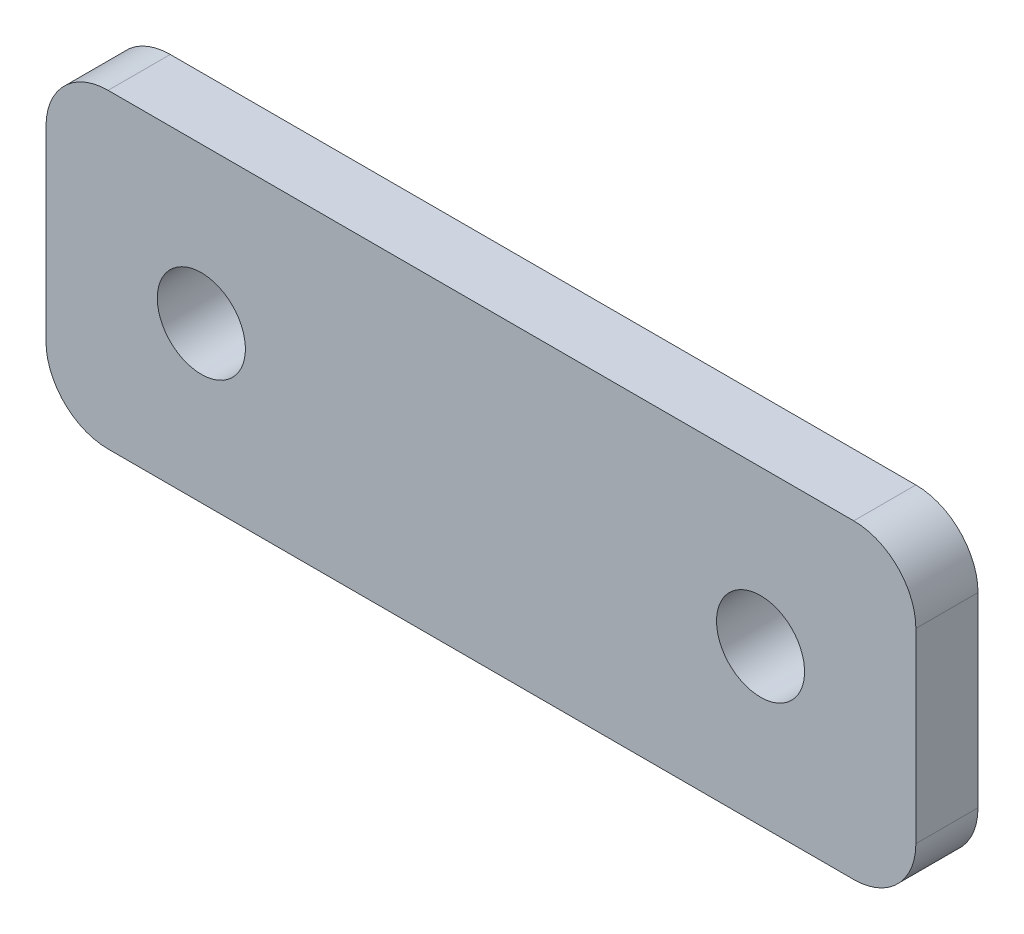
SolidWorks part; units mm, degrees
material "6061-T6 (SS)"
ref_plane "X-Y Datum" through (0, 0, 0) normal (0, 0, 1) x (1, 0, 0)
ref_plane "X-Z Datum" through (0, 0, 0) normal (0, 1, 0) x (1, 0, 0)
ref_plane "Y-Z Datum" through (0, 0, 0) normal (1, 0, 0) x (0, 0, -1)
sketch "Sketch1" plane through (0, 0, 0) normal (0, 0, 1) x (1, 0, 0)
  line L0 (-14.2875, 0) -> (14.2875, 0) construction
  line L2 (-22.225, 7.9375) -> (22.225, 7.9375)
  line L3 (-22.225, 7.9375) -> (-22.225, -7.9375)
  line L4 (-22.225, -7.9375) -> (22.225, -7.9375)
  line L5 (22.225, 7.9375) -> (22.225, -7.9375)
  line L6 (-22.225, 7.9375) -> (22.225, -7.9375) construction
  line L7 (-22.225, -7.9375) -> (22.225, 7.9375) construction
  circle A0 centre (14.2875, 0) radius 2 construction
  circle A1 centre (-14.2875, 0) radius 2 construction
  point P4 (0, 0)
  point P7 (0, 0)
  dimension "D2" = 4
  dimension "D1" = 28.575
  dimension "D3" = 44.45
  dimension "D4" = 15.875
extrude "Boss-Extrude1" add sketch "Sketch1" along normal blind 3.175
hole_wizard "M4 Clearance Hole1" positions "Sketch4" profile "Sketch3" hole size "M4" standard "ANSI Metric" end condition through all
sketch "Sketch4" plane through (0, 0, 0) normal (0, 0, -1) x (-1, 0, 0)
  point P0 (-14.2875, 0)
  point P3 (14.2875, 0)
sketch "Sketch3" plane through (14.2875, 0, 0) normal (1, 0, 0) x (0, 1, 0)
  line L0 (0, 0) -> (0, 3.175)
  line L1 (0, 3.175) -> (2.25, 3.175)
  line L2 (2.25, 3.175) -> (2.25, 0)
  line L5 (2.25, 0) -> (0, 0)
  line L11 (0, -6.35) -> (0, 107.95) construction
  dimension "Thru Hole Dia." = 4.5
  dimension "Thru Hole Depth" = 3.175
fillet "Fillet1" radius 3.175 4 edges at (-22.225, 7.9375, 1.5875) (-22.225, -7.9375, 1.5875) (22.225, -7.9375, 1.5875) (22.225, 7.9375, 1.5875)
